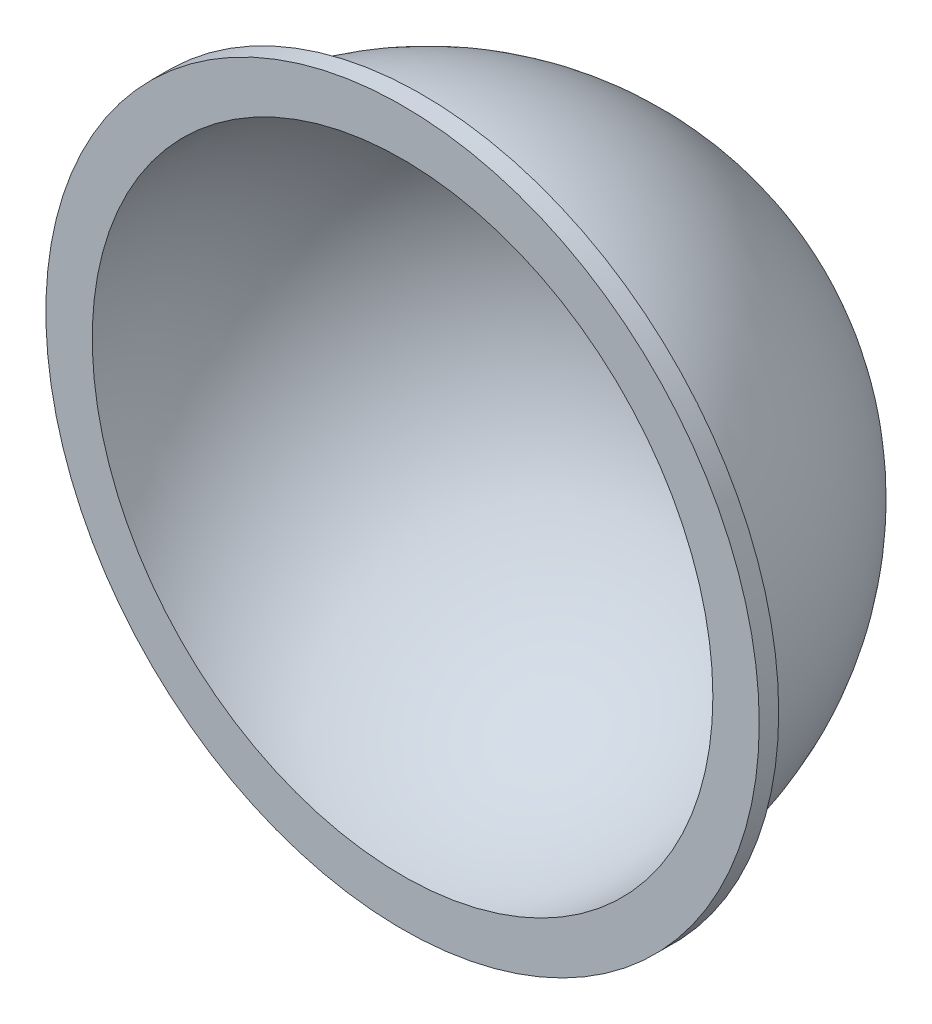
SolidWorks part; units mm, degrees
material "PC High Viscosity"
ref_plane "Front Plane" through (0, 0, 0) normal (0, 0, 1) x (1, 0, 0)
ref_plane "Top Plane" through (0, 0, 0) normal (0, 1, 0) x (1, 0, 0)
ref_plane "Right Plane" through (0, 0, 0) normal (1, 0, 0) x (0, 0, -1)
sketch "Sketch2" plane through (0, 0, 0) normal (0, 1, 0) x (1, 0, 0)
  line L0 (-55, 0) -> (-47.8481, 0)
  line L1 (-55, 0) -> (-55, 3)
  line L2 (-55, 3) -> (-50, 3)
  line L3 (0, 55) -> (0, 44.7083)
  line L4 (0, 0) -> (0, 68.0025) construction
  arc A0 (-47.8481, 0) -> (0, 44.7083) centre (-3.0368, 0) cw
  arc A1 (-50, 3) -> (0, 55) centre (2.04, 3) cw
  dimension "D3" = 3
  dimension "D1" = 50
  dimension "D2" = 55
  dimension "D5" = 55
revolve "Revolve1" add sketch "Sketch2" angle 360 about L4
